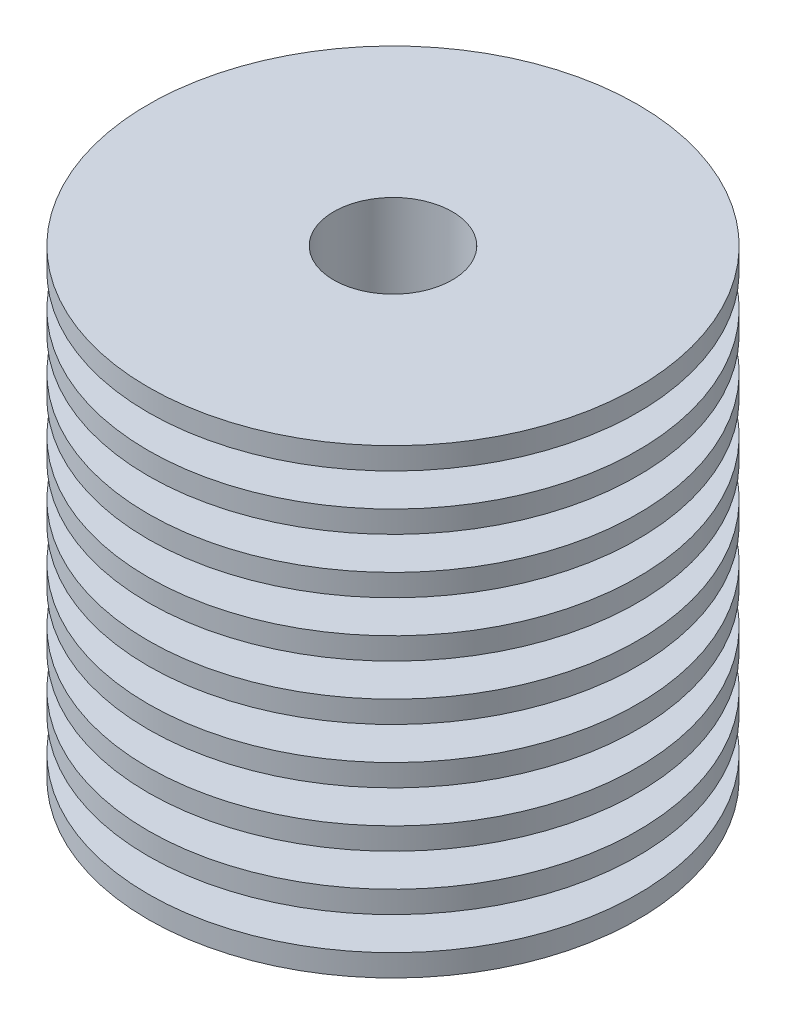
SolidWorks part; units mm, degrees
material "1060 Alloy"
ref_plane "Front Plane" through (0, 0, 0) normal (0, 0, 1) x (1, 0, 0)
ref_plane "Top Plane" through (0, 0, 0) normal (0, 1, 0) x (1, 0, 0)
ref_plane "Right Plane" through (0, 0, 0) normal (1, 0, 0) x (0, 0, -1)
sketch "Sketch1" plane through (0, 0, 0) normal (0, 0, 1) x (1, 0, 0)
  line L0 (11.15, 18.5) -> (5.0829, 18.5)
  line L1 (5.0829, 18.5) -> (5.0829, 20)
  line L2 (5.0829, 20) -> (11.15, 20)
  line L3 (11.15, 20) -> (11.15, 21)
  line L4 (11.15, 21) -> (4.9518, 21)
  line L5 (4.9518, 21) -> (4.9518, 22.5)
  line L6 (4.9518, 22.5) -> (11.15, 22.5)
  line L7 (11.15, 22.5) -> (11.15, 23.5)
  line L8 (11.15, 23.5) -> (4.8208, 23.5)
  line L9 (4.8208, 23.5) -> (4.8208, 25)
  line L10 (4.8208, 25) -> (11.15, 25)
  line L11 (11.15, 25) -> (11.15, 26)
  line L12 (11.15, 26) -> (4.6898, 26)
  line L13 (4.6898, 26) -> (4.6898, 27.5)
  line L14 (4.6898, 27.5) -> (8, 27.5)
  line L15 (8, 27.5) -> (8, 28.5)
  line L16 (8, 28.5) -> (4.6898, 28.5)
  line L17 (4.6898, 28.5) -> (4.6898, 30)
  line L18 (4.6898, 30) -> (8, 30)
  line L19 (8, 30) -> (8, 33)
  line L20 (8, 33) -> (6, 33)
  line L21 (6, 33) -> (6, 39)
  line L22 (6, 39) -> (8, 39)
  line L23 (8, 39) -> (8, 42.7)
  line L24 (8, 42.7) -> (4, 42.7)
  line L25 (4, 42.7) -> (4, 36.6)
  line L26 (4, 36.6) -> (2.1, 34.7)
  line L27 (2.1, 34.7) -> (2.1, 14.7)
  line L28 (2.1, 14.7) -> (3.5, 13.3)
  line L29 (3.5, 13.3) -> (3.5, 0)
  line L30 (3.5, 0) -> (11.15, 0)
  line L31 (11.15, 0) -> (11.15, 1)
  line L32 (11.15, 1) -> (6, 1)
  line L33 (6, 1) -> (6, 2.5)
  line L34 (6, 2.5) -> (11.15, 2.5)
  line L35 (11.15, 2.5) -> (11.15, 3.5)
  line L36 (11.15, 3.5) -> (5.869, 3.5)
  line L37 (5.869, 3.5) -> (5.869, 5)
  line L38 (5.869, 5) -> (11.15, 5)
  line L39 (11.15, 5) -> (11.15, 6)
  line L40 (11.15, 6) -> (5.738, 6)
  line L41 (5.738, 6) -> (5.738, 7.5)
  line L42 (5.738, 7.5) -> (11.15, 7.5)
  line L43 (11.15, 7.5) -> (11.15, 8.5)
  line L44 (11.15, 8.5) -> (5.6069, 8.5)
  line L45 (5.6069, 8.5) -> (5.6069, 10)
  line L46 (5.6069, 10) -> (11.15, 10)
  line L47 (11.15, 10) -> (11.15, 11)
  line L48 (11.15, 11) -> (5.4759, 11)
  line L49 (5.4759, 11) -> (5.4759, 12.5)
  line L50 (5.4759, 12.5) -> (11.15, 12.5)
  line L51 (11.15, 12.5) -> (11.15, 13.5)
  line L52 (11.15, 13.5) -> (5.3449, 13.5)
  line L53 (5.3449, 13.5) -> (5.3449, 15)
  line L54 (5.3449, 15) -> (11.15, 15)
  line L55 (11.15, 15) -> (11.15, 16)
  line L56 (11.15, 16) -> (5.2139, 16)
  line L57 (5.2139, 16) -> (5.2139, 17.5)
  line L58 (5.2139, 17.5) -> (11.15, 17.5)
  line L59 (11.15, 17.5) -> (11.15, 18.5)
  line L60 (0, 42.7) -> (0, 0) construction
revolve "Revolve1" add sketch "Sketch1" angle 360 about L60
sketch "Эскиз1" plane through (0, 21, 0) normal (0, 1, 0) x (1, 0, 0)
  circle A0 centre (0, 0) radius 11.3096
extrude "Вырез-Вытянуть1" cut sketch "Эскиз1" along normal up to next
sketch "Эскиз2" plane through (0, 21, 0) normal (0, 1, 0) x (1, 0, 0)
  circle A0 centre (0, 0) radius 2.7
extrude "Вырез-Вытянуть2" cut sketch "Эскиз2" against normal up to next
